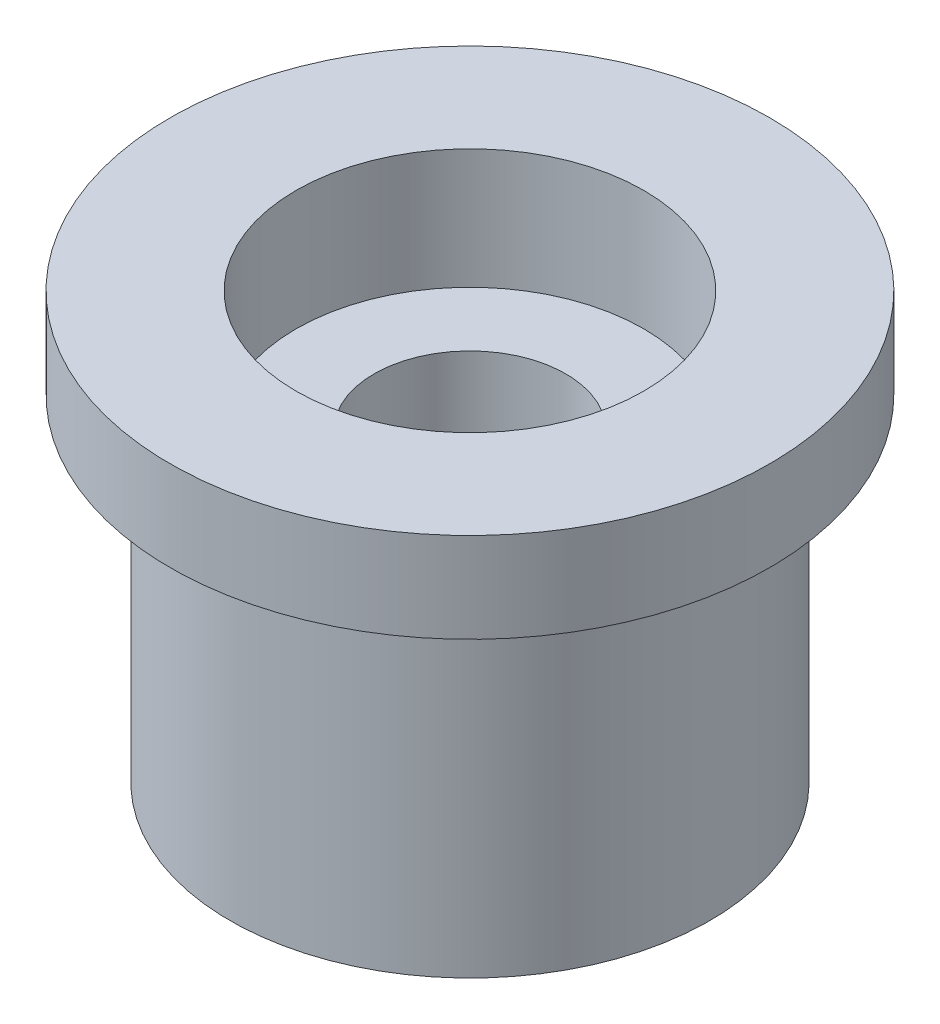
SolidWorks part; units mm, degrees
ref_plane "Plan de face" through (0, 0, 0) normal (0, 0, 1) x (1, 0, 0)
ref_plane "Plan de dessus" through (0, 0, 0) normal (0, 1, 0) x (1, 0, 0)
ref_plane "Plan de droite" through (0, 0, 0) normal (1, 0, 0) x (0, 0, -1)
sketch "Esquisse1" plane through (0, 0, 0) normal (0, 0, 1) x (1, 0, 0)
  line L0 (5, 7.1) -> (0, 7.1)
  line L1 (0, 7.1) -> (0, 5.6)
  line L2 (0, 5.6) -> (5, 5.6)
  line L3 (5, 5.6) -> (5, 7.1)
  line L4 (0, 7.1) -> (0, 5.6) construction
revolve "Révolution1" add sketch "Esquisse1" angle 360 about L4
sketch "Esquisse2" plane through (0, 5.6, 0) normal (0, -1, 0) x (1, 0, 0)
  circle A0 centre (0, 0) radius 4
extrude "Boss.-Extru.1" add sketch "Esquisse2" along normal blind 5.6
sketch "Esquisse3" plane through (0, 0, 0) normal (0, -1, 0) x (1, 0, 0)
  line L0 (-1.1906, 2.8622) -> (-0.7861, 2.1615)
  line L1 (2.265, 0.4) -> (3.0741, 0.4)
  arc A0 (-0.7861, 2.1615) -> (2.265, 0.4) centre (0, 0) cw
  arc A1 (3.0741, 0.4) -> (-1.1906, 2.8622) centre (0, 0) ccw
extrude "Enlèv. mat.-Extru.1" cut sketch "Esquisse3" against normal blind 4.3
sketch "Esquisse4" plane through (0, 0, 0) normal (0, -1, 0) x (1, 0, 0)
  line L0 (-0.7861, -2.1615) -> (-1.1906, -2.8622)
  line L1 (3.0741, -0.4) -> (2.265, -0.4)
  arc A0 (-1.1906, -2.8622) -> (3.0741, -0.4) centre (0, 0) ccw
  arc A1 (2.265, -0.4) -> (-0.7861, -2.1615) centre (0, 0) cw
extrude "Enlèv. mat.-Extru.2" cut sketch "Esquisse4" against normal blind 4.3
sketch "Esquisse5" plane through (0, 0, 0) normal (0, -1, 0) x (1, 0, 0)
  line L0 (-1.8835, -2.4622) -> (-1.4789, -1.7615)
  line L1 (-1.4789, 1.7615) -> (-1.8835, 2.4622)
  arc A0 (-1.4789, -1.7615) -> (-1.4789, 1.7615) centre (0, 0) cw
  arc A1 (-1.8835, 2.4622) -> (-1.8835, -2.4622) centre (0, 0) ccw
extrude "Enlèv. mat.-Extru.3" cut sketch "Esquisse5" against normal blind 4.3
hole_wizard "Chambrage pour vis à tête hexagonale M31" positions "Esquisse7" profile "Esquisse6" counterbore size "M3" standard "Ansi Metric"
sketch "Esquisse7" plane through (0, 7.1, 0) normal (0, 1, 0) x (1, 0, 0)
  point P0 (0, 0)
sketch "Esquisse6" plane through (0, 7.1, 0) normal (1, 0, 0) x (0, 0, 1)
  line L0 (0, 0) -> (0, 7.1)
  line L1 (0, 7.1) -> (1.6, 7.1)
  line L3 (1.6, 7.1) -> (1.6, 2)
  line L4 (1.6, 2) -> (2.9, 2)
  line L5 (2.9, 2) -> (2.9, 0)
  line L7 (2.9, 0) -> (0, 0)
  line L11 (0, -6.35) -> (0, 107.95) construction
  dimension "Diamètre du perçage jusqu'au prochain" = 3.2
  dimension "Profondeur du perçage jusqu'au prochain" = 7.1
  dimension "Diamètre du chambrage" = 5.8
  dimension "Profondeur du chambrage" = 2
